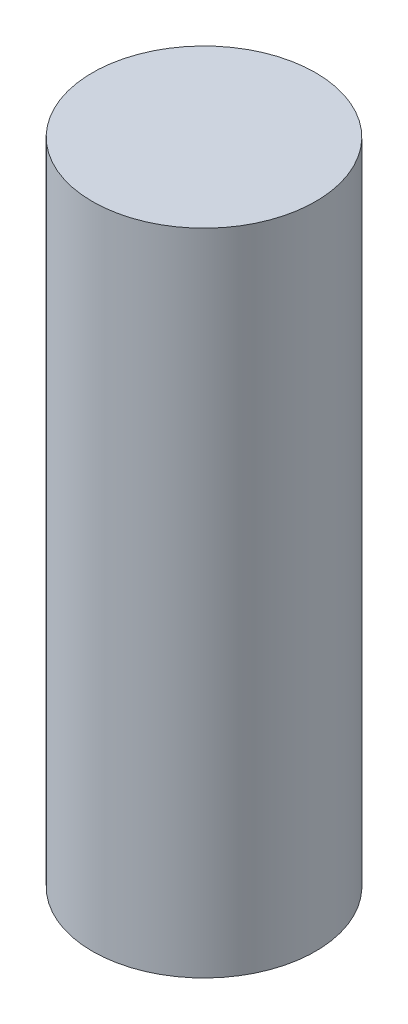
SolidWorks part; units mm, degrees
ref_plane "Front Plane" through (0, 0, 0) normal (0, 0, 1) x (1, 0, 0)
ref_plane "Top Plane" through (0, 0, 0) normal (0, 1, 0) x (1, 0, 0)
ref_plane "Right Plane" through (0, 0, 0) normal (1, 0, 0) x (0, 0, -1)
sketch "Sketch1" plane through (0, 0, 0) normal (0, 1, 0) x (1, 0, 0)
  circle A0 centre (0, 0) radius 27.5
  dimension "D1" = 55
extrude "Boss-Extrude1" add sketch "Sketch1" along normal blind 160
